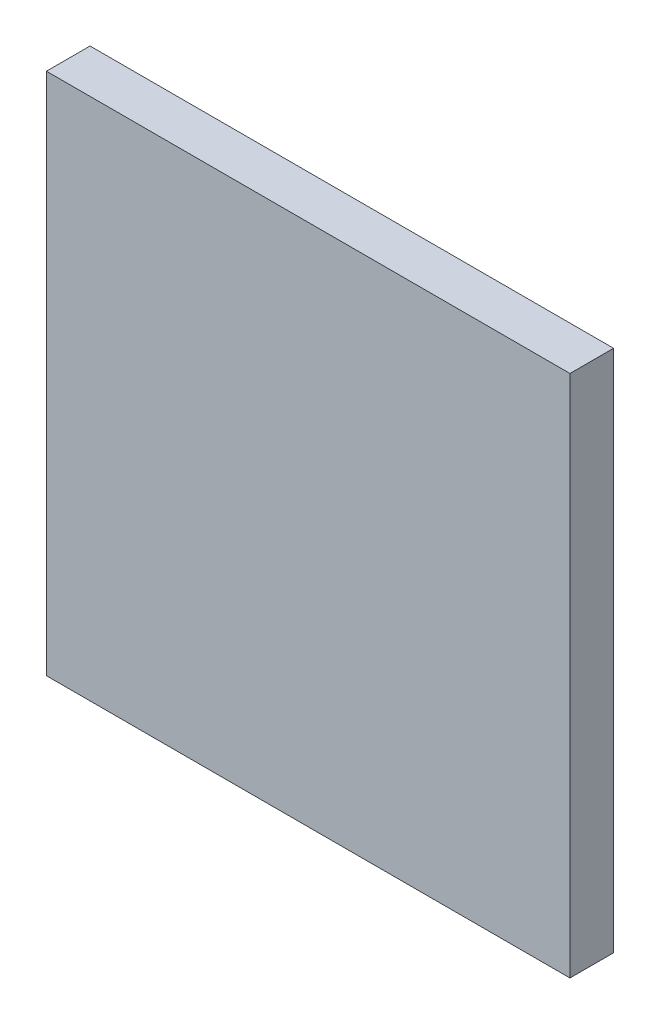
SolidWorks part; units mm, degrees
ref_plane "Front" through (0, 0, 0) normal (0, 0, 1) x (1, 0, 0)
ref_plane "Top" through (0, 0, 0) normal (0, 1, 0) x (1, 0, 0)
ref_plane "Right" through (0, 0, 0) normal (1, 0, 0) x (0, 0, -1)
other "Configuration Table"
sketch "Sketch1" plane through (0, 0, 0) normal (0, 0, 1) x (1, 0, 0)
  line L1 (0, 0) -> (6, 0)
  line L2 (0, 0) -> (0, 6)
  line L3 (0, 6) -> (6, 6)
  line L4 (6, 0) -> (6, 6)
  dimension "D1" = 6
  dimension "D2" = 6
extrude "Extrude1" add sketch "Sketch1" against normal blind 0.5
